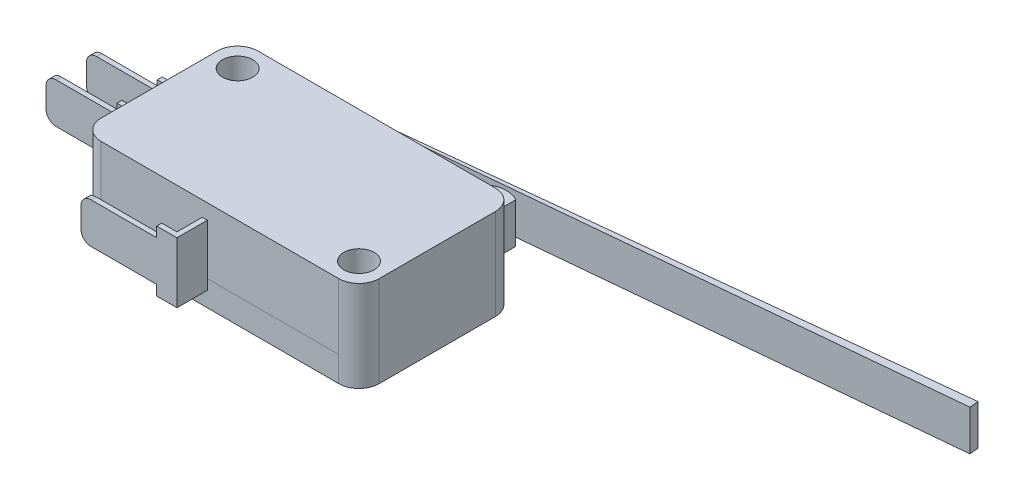
SolidWorks part; units mm, degrees
ref_plane "Front Plane" through (0, 0, 0) normal (0, 0, 1) x (1, 0, 0)
ref_plane "Top Plane" through (0, 0, 0) normal (0, 1, 0) x (1, 0, 0)
ref_plane "Right Plane" through (0, 0, 0) normal (1, 0, 0) x (0, 0, -1)
sketch "Sketch1" plane through (0, 0, 0) normal (0, 1, 0) x (1, 0, 0)
  line L1 (11.75, -7.75) -> (-11.75, -7.75)
  line L2 (13.75, -5.75) -> (13.75, 5.75)
  line L3 (11.75, 7.75) -> (-11.75, 7.75)
  line L4 (-13.75, -5.75) -> (-13.75, 5.75)
  line L5 (13.75, -7.75) -> (-13.75, 7.75) construction
  line L6 (13.75, 7.75) -> (-13.75, -7.75) construction
  circle A0 centre (-11.25, 5.25) radius 1.5
  arc A1 (-11.75, 7.75) -> (-13.75, 5.75) centre (-11.75, 5.75) ccw
  arc A2 (11.75, -7.75) -> (13.75, -5.75) centre (11.75, -5.75) ccw
  circle A3 centre (11.25, -5.25) radius 1.5
  arc A4 (13.75, 5.75) -> (11.75, 7.75) centre (11.75, 5.75) ccw
  arc A5 (-11.75, -7.75) -> (-13.75, -5.75) centre (-11.75, -5.75) cw
  point P0 (0, 0)
  point P8 (-11.25, 6.75)
  point P9 (-12.75, 5.25)
  point P18 (11.25, -6.75)
  point P19 (12.75, -5.25)
  dimension "D3" = 3
  dimension "D6" = 2
  dimension "D7" = 2
  dimension "D8" = 3
  dimension "D11" = 2
  dimension "D1" = 27.5
  dimension "D2" = 15.5
  dimension "D4" = 1
  dimension "D5" = 1
  dimension "D9" = 1
  dimension "D10" = 1
extrude "Boss-Extrude1" add sketch "Sketch1" along normal blind 9
sketch "Sketch2" plane through (0, 0, 7.75) normal (0, 0, 1) x (1, 0, 0)
  line L0 (-13.75, 2.5) -> (13.7248, 2.5)
  line L1 (-13.75, 9) -> (-13.75, 0) construction
  line L2 (-11.75, 0) -> (11.75, 0) construction
  dimension "D1" = 2.5
split line "Split Line2"
ref_plane "Plane1" through (0, 2.5, 0) normal (0, -1, 0) x (-1, 0, 0)
sketch "Sketch3" plane through (0, 2.5, 0) normal (0, -1, 0) x (-1, 0, 0)
  line L0 (-11.25, 7.75) -> (-11.25, 10.25)
  line L1 (-11.75, 7.75) -> (11.75, 7.75) construction
  line L3 (-8.75, 10.25) -> (-8.75, 7.75)
  line L4 (-8.75, 7.75) -> (-11.25, 7.75)
  line L5 (-13.75, -5.75) -> (-13.75, 5.75) construction
  arc A0 (-11.25, 10.25) -> (-8.75, 10.25) centre (-10, 8.0849) cw
  dimension "D4" = 2.5
  dimension "D1" = 2.5
  dimension "D2" = 2.5
  dimension "D3" = 2.5
extrude "Boss-Extrude2" add sketch "Sketch3" against normal blind 4
sketch "Sketch4" plane through (0, 2.5, 0) normal (0, -1, 0) x (-1, 0, 0)
  line L0 (1.75, 7.75) -> (2.205, 7.75)
  line L1 (-11.75, 7.75) -> (11.75, 7.75) construction
  line L3 (2.205, 7.75) -> (2.205, 10.0695)
  line L4 (1.75, 7.75) -> (1.75, 9.8792)
  line L5 (1.75, 9.8792) -> (-51.4762, 14.9532)
  line L6 (2.205, 10.0695) -> (-51.3927, 15.8293)
  line L7 (-51.3927, 15.8293) -> (-51.4762, 14.9532)
  point P11 (1.75, 10.0057)
  point P12 (-51.6459, 14.969)
extrude "Boss-Extrude9" add sketch "Sketch4" against normal blind 4
ref_plane "Plane2" through (0, 1.5, 0) normal (0, -1, 0) x (-1, 0, 0)
sketch "Sketch5" plane through (0, 1.5, 0) normal (0, -1, 0) x (-1, 0, 0)
  line L0 (1.75, -7.75) -> (1.75, -10.25)
  line L1 (11.75, -7.75) -> (-11.75, -7.75) construction
  line L2 (1.75, -10.25) -> (10.75, -10.25)
  line L3 (1.25, -7.75) -> (1.25, -10.75)
  line L4 (1.25, -10.75) -> (10.75, -10.75)
  line L5 (1.25, -7.75) -> (1.75, -7.75)
  line L6 (10.75, -10.25) -> (10.75, -10.75)
  line L7 (13.75, 2.299) -> (22.75, 2.299)
  line L8 (13.75, 5.75) -> (13.75, -5.75) construction
  line L9 (13.75, -1.701) -> (22.75, -1.701)
  line L10 (13.75, 1.799) -> (22.75, 1.799)
  line L11 (13.75, -2.201) -> (22.75, -2.201)
  line L12 (13.75, 2.299) -> (13.75, 1.799)
  line L13 (13.75, -1.701) -> (13.75, -2.201)
  line L14 (22.75, -2.201) -> (22.75, -1.701)
  line L15 (22.75, 1.799) -> (22.75, 2.299)
  dimension "D1" = 2.5
  dimension "D2" = 9
  dimension "D4" = 9
  dimension "D5" = 9
  dimension "D6" = 4
  dimension "D3" = 0.5
  dimension "D7" = 0.5
extrude "Boss-Extrude10" add sketch "Sketch5" against normal blind 6
sketch "Sketch6" plane through (0, 0, 10.75) normal (0, 0, 1) x (1, 0, 0)
  line L1 (-3.25, 1.5) -> (-3.25, 2.5)
  line L2 (-1.25, 1.5) -> (-10.75, 1.5) construction
  line L3 (-3.25, 2.5) -> (-10.75, 2.5)
  line L4 (-10.75, 7.5) -> (-10.75, 1.5) construction
  line L5 (-1.25, 2.5) -> (-1.25, 1.5) construction
  line L6 (-1.25, 4.5) -> (-10.75, 4.5) construction
  line L7 (-1.25, 7.5) -> (-1.25, 1.5) construction
  line L8 (-3.25, 6.5) -> (-10.75, 6.5)
  line L9 (-3.25, 7.5) -> (-3.25, 6.5)
  line L10 (-3.25, 1.5) -> (-10.75, 1.5)
  line L11 (-10.75, 1.5) -> (-10.75, 2.5)
  line L12 (-10.75, 6.5) -> (-10.75, 7.5)
  line L13 (-10.75, 7.5) -> (-3.25, 7.5)
  dimension "D1" = 1
  dimension "D2" = 2
extrude "Cut-Extrude1" cut sketch "Sketch6" against normal blind 2
sketch "Sketch7" plane through (0, 0, 2.201) normal (0, 0, 1) x (1, 0, 0)
  line L0 (-15.75, 1.5) -> (-15.75, 2.5)
  line L1 (-13.75, 1.5) -> (-22.75, 1.5) construction
  line L2 (-15.75, 2.5) -> (-22.75, 2.5)
  line L3 (-22.75, 7.5) -> (-22.75, 1.5) construction
  line L4 (-13.75, 2.5) -> (-13.75, 1.5) construction
  line L5 (-15.75, 7.5) -> (-15.75, 6.5)
  line L6 (-13.75, 7.5) -> (-22.75, 7.5) construction
  line L7 (-15.75, 6.5) -> (-22.75, 6.5)
  line L8 (-22.75, 6.5) -> (-22.75, 7.5)
  line L9 (-22.75, 7.5) -> (-15.75, 7.5)
  line L10 (-15.75, 1.5) -> (-22.75, 1.5)
  line L11 (-22.75, 1.5) -> (-22.75, 2.5)
  point P4 (-13.75, 2)
  dimension "D1" = 2
extrude "Cut-Extrude2" cut sketch "Sketch7" against normal blind 5
fillet "Fillet1" radius 1 6 edges at (-22.75, 2.5, -2.049) (-22.75, 6.5, -2.049) (-22.75, 2.5, 1.951) (-22.75, 6.5, 1.951) (-10.75, 6.5, 10.5) (-10.75, 2.5, 10.5)
